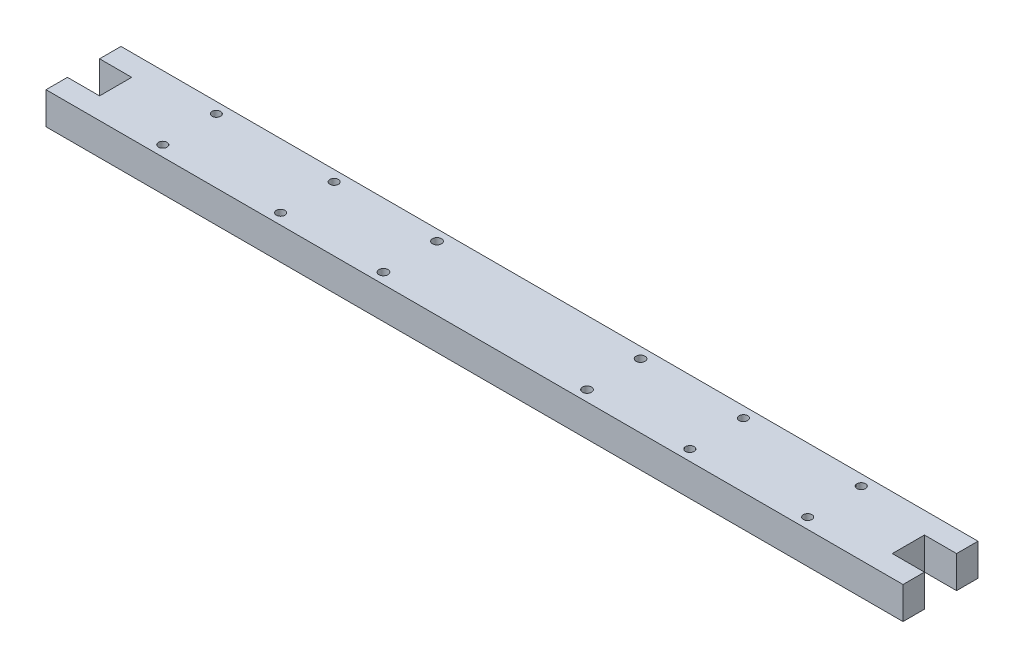
SolidWorks part; units mm, degrees
ref_plane "前视基准面" through (0, 0, 0) normal (0, 0, 1) x (1, 0, 0)
ref_plane "上视基准面" through (0, 0, 0) normal (0, 1, 0) x (1, 0, 0)
ref_plane "右视基准面" through (0, 0, 0) normal (1, 0, 0) x (0, 0, -1)
sketch "草图3" plane through (0, 0, 0) normal (0, 1, 0) x (1, 0, 0)
  line L0 (0, 0) -> (400, 0)
  line L1 (0, 0) -> (0, 10)
  line L2 (400, 0) -> (400, 10)
  line L3 (0, 35) -> (400, 35)
  line L4 (0, 10) -> (15, 10)
  line L6 (15, 10) -> (15, 25)
  line L7 (0, 25) -> (15, 25)
  line L8 (0, 25) -> (0, 35)
  line L10 (400, 10) -> (385, 10)
  line L11 (400, 25) -> (385, 25)
  line L12 (385, 10) -> (385, 25)
  line L13 (400, 25) -> (400, 35)
  dimension "D1" = 10
  dimension "D2" = 10
  dimension "D3" = 10
  dimension "D4" = 15
  dimension "D5" = 10
  dimension "D6" = 15
  dimension "D7" = 400
  dimension "D8" = 15
  dimension "D9" = 15
  dimension "D10" = 15
extrude "凸台-拉伸1" add sketch "草图3" along normal blind 15 contours L3 L13 L11 L12 L10 L2 L0 L1 L4 L6 L7 L8
sketch "草图5" plane through (0, 15, 0) normal (0, 1, 0) x (1, 0, 0)
  line L0 (0, 35) -> (400, 35) construction
  line L2 (0, 25) -> (0, 35) construction
  circle A0 centre (152.5, 5) radius 2.1
  circle A1 centre (152.5, 30) radius 2.1
  circle A2 centre (247.5, 5) radius 2.1
  circle A3 centre (247.5, 30) radius 2.1
  point P0 (200, 17.5)
  point P7 (200, 17.5)
  dimension "D1" = 17.5
  dimension "D2" = 200
extrude "切除-拉伸2" cut sketch "草图5" against normal blind 30
sketch "草图6" plane through (0, 15, 0) normal (0, 1, 0) x (1, 0, 0)
  line L1 (350.5, 5) -> (295.5, 5) construction
  line L2 (350.5, 5) -> (350.5, 30) construction
  line L3 (350.5, 30) -> (295.5, 30) construction
  line L4 (295.5, 5) -> (295.5, 30) construction
  line L5 (350.5, 5) -> (295.5, 30) construction
  line L6 (350.5, 30) -> (295.5, 5) construction
  line L7 (200, 0) -> (200, 35) construction
  line L8 (0, 0) -> (400, 0) construction
  line L9 (0, 35) -> (400, 35) construction
  line L11 (400, 25) -> (400, 35) construction
  line L13 (49.5, 30) -> (104.5, 30) construction
  line L14 (49.5, 30) -> (49.5, 5) construction
  line L15 (49.5, 5) -> (104.5, 5) construction
  line L16 (104.5, 30) -> (104.5, 5) construction
  circle A0 centre (350.5, 5) radius 2
  circle A1 centre (295.5, 5) radius 2
  circle A2 centre (350.5, 30) radius 2
  circle A3 centre (295.5, 30) radius 2
  circle A4 centre (49.5, 30) radius 2
  circle A5 centre (104.5, 30) radius 2
  circle A6 centre (104.5, 5) radius 2
  circle A7 centre (49.5, 5) radius 2
  point P0 (323, 17.5)
  dimension "D4" = 17.5
  dimension "D1" = 55
  dimension "D2" = 25
  dimension "D3" = 77
extrude "切除-拉伸3" cut sketch "草图6" against normal blind 15
